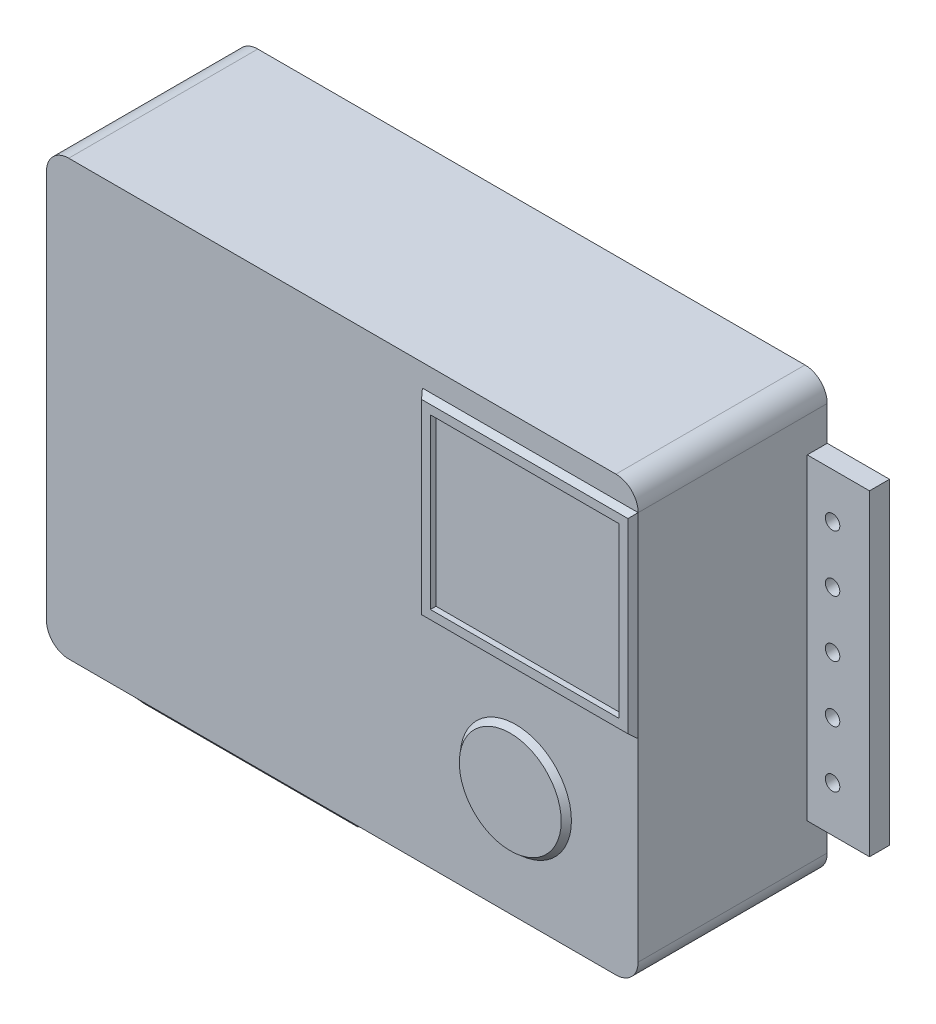
SolidWorks part; units mm, degrees
ref_plane "Front Plane" through (0, 0, 0) normal (0, 0, 1) x (1, 0, 0)
ref_plane "Top Plane" through (0, 0, 0) normal (0, 1, 0) x (1, 0, 0)
ref_plane "Right Plane" through (0, 0, 0) normal (1, 0, 0) x (0, 0, -1)
sketch "Sketch1" plane through (0, 0, 0) normal (0, 0, 1) x (1, 0, 0)
  line L0 (0, 9.75) -> (0, -9.75) construction
  line L1 (-13.3, 9.75) -> (13.3, 9.75)
  line L2 (-13.3, 9.75) -> (-13.3, -9.75)
  line L3 (-13.3, -9.75) -> (13.3, -9.75)
  line L4 (13.3, 9.75) -> (13.3, -9.75)
  point P6 (0, 0)
  point P7 (0, 0)
  dimension "D1" = 26.6
  dimension "D2" = 19.5
extrude "Base" add sketch "Sketch1" along normal blind 8.5
sketch "Sketch2" plane through (0, 0, 8.5) normal (0, 0, 1) x (1, 0, 0)
  line L0 (13.3, -9.75) -> (13.3, 9.75) construction
  line L1 (3.6, 8.75) -> (13.3, 8.75)
  line L2 (3.6, 8.75) -> (3.6, -0.05)
  line L3 (3.6, -0.05) -> (13.3, -0.05)
  line L4 (13.3, 8.75) -> (13.3, -0.05)
  line L6 (13.3, 9.75) -> (-13.3, 9.75) construction
  line L7 (-13.3, -9.75) -> (13.3, -9.75) construction
  circle A0 centre (7.8, -4.75) radius 2.5
  dimension "D1" = 5
  dimension "D5" = 5
  dimension "D6" = 5.5
  dimension "D2" = 8.8
  dimension "D3" = 9.7
  dimension "D4" = 1
extrude "Boss-Extrude2" add sketch "Sketch2" along normal blind 0.25 draft 40
sketch "Sketch3" plane through (0, 0, 8.75) normal (0, 0, 1) x (1, 0, 0)
  line L8 (12.6902, 8.1402) -> (4.2098, 8.1402)
  line L9 (12.6902, 0.5598) -> (12.6902, 8.1402)
  line L10 (4.2098, 0.5598) -> (12.6902, 0.5598)
  line L11 (4.2098, 8.1402) -> (4.2098, 0.5598)
  line L12 (12.6902, 8.1402) -> (4.2098, 8.1402)
  line L13 (12.6902, 0.5598) -> (12.6902, 8.1402)
  line L14 (4.2098, 0.5598) -> (12.6902, 0.5598)
  line L15 (4.2098, 8.1402) -> (4.2098, 0.5598)
  dimension "D1" = 0.4
extrude "Cut-Extrude1" cut sketch "Sketch3" against normal up to surface (0.25 mm away) up to face at (10.3, -4.75, 8.5)
sketch "Sketch4" plane through (0, -9.75, 0) normal (0, -1, 0) x (1, 0, 0)
  line L0 (-13.3, 8.5) -> (13.3, 8.5) construction
  line L1 (-9.3, 8.5) -> (0.7, 8.5)
  line L2 (-9.3, 8.5) -> (-9.3, 0)
  line L3 (-9.3, 0) -> (0.7, 0)
  line L4 (0.7, 8.5) -> (0.7, 0)
  line L5 (-13.3, 0) -> (13.3, 0) construction
  line L6 (-13.3, 8.5) -> (-13.3, 0) construction
  dimension "D1" = 10
  dimension "D2" = 4
extrude "Boss-Extrude3" add sketch "Sketch4" along normal blind 0.25 draft 40
sketch "Sketch5" plane through (0, -10, 0) normal (0, -1, 0) x (1, 0, 0)
  line L8 (-8.7902, 7.9902) -> (-8.7902, 0.5098)
  line L9 (-8.7902, 0.5098) -> (0.1902, 0.5098)
  line L10 (0.1902, 0.5098) -> (0.1902, 7.9902)
  line L11 (0.1902, 7.9902) -> (-8.7902, 7.9902)
  line L12 (-8.7902, 7.9902) -> (-8.7902, 0.5098)
  line L13 (-8.7902, 0.5098) -> (0.1902, 0.5098)
  line L14 (0.1902, 0.5098) -> (0.1902, 7.9902)
  line L15 (0.1902, 7.9902) -> (-8.7902, 7.9902)
  dimension "D1" = 0.3
extrude "Cut-Extrude2" cut sketch "Sketch5" against normal up to surface (0.25 mm away) up to face at (-11.3, -9.75, 4.25)
fillet "Fillet1" radius 1 4 edges at (13.3, 9.75, 4.25) (13.3, -9.75, 4.25) (-13.3, 9.75, 4.25) (-13.3, -9.75, 4.25)
sketch "Sketch6" plane through (0, 0, 0) normal (0, 0, -1) x (-1, 0, 0)
  line L0 (-12.3, 9.75) -> (12.3, 9.75) construction
  line L1 (4.2, 3.55) -> (-2.3, 3.55)
  line L2 (4.2, 3.55) -> (4.2, 6.05)
  line L3 (4.2, 6.05) -> (-2.3, 6.05)
  line L4 (-2.3, 3.55) -> (-2.3, 6.05)
  line L5 (13.3, 8.75) -> (13.3, -8.75) construction
  dimension "D1" = 6.5
  dimension "D2" = 2.5
  dimension "D3" = 3.7
  dimension "D4" = 9.1
extrude "Connector1" add sketch "Sketch6" along normal blind 0.2
sketch "Sketch7" plane through (0, 0, -0.2) normal (0, 0, -1) x (-1, 0, 0)
  line L1 (3.2, 3.7) -> (-1.3, 3.7)
  line L2 (3.2, 3.7) -> (3.2, 5.9)
  line L3 (3.2, 5.9) -> (-1.3, 5.9)
  line L4 (-1.3, 3.7) -> (-1.3, 5.9)
  line L6 (0.95, 6.05) -> (0.95, 3.55) construction
  line L7 (4.2, 6.05) -> (-2.3, 6.05) construction
  line L8 (-2.3, 3.55) -> (4.2, 3.55) construction
  line L9 (0.95, 3.7) -> (0.95, 5.9) construction
  point P8 (0.9, 6.05)
  point P9 (0.95, 4.8)
  point P14 (0, 0)
  point P15 (0.95, 4.8)
  dimension "D1" = 4.5
  dimension "D2" = 2.2
extrude "Connector2" add sketch "Sketch7" along normal blind 0.25
sketch "Sketch8" plane through (0, 0, 0) normal (0, 0, -1) x (-1, 0, 0)
  line L0 (13.3, 8.75) -> (13.3, -8.75) construction
  line L1 (13.3, -7.75) -> (16.6, -7.75)
  line L2 (13.3, -7.75) -> (13.3, 5.25)
  line L3 (13.3, 5.25) -> (16.6, 5.25)
  line L4 (16.6, -7.75) -> (16.6, 5.25)
  line L5 (-13.3, -8.75) -> (-13.3, 8.75) construction
  line L6 (-13.3, -7.05) -> (-16.1, -7.05)
  line L7 (-13.3, -7.05) -> (-13.3, 7.2)
  line L8 (-13.3, 7.2) -> (-16.1, 7.2)
  line L9 (-16.1, -7.05) -> (-16.1, 7.2)
  line L10 (12.3, -9.75) -> (9.3, -9.75) construction
  line L11 (-0.7, -9.75) -> (-12.3, -9.75) construction
  dimension "D1" = 13
  dimension "D2" = 14.25
  dimension "D3" = 2
  dimension "D4" = 3.3
  dimension "D5" = 2.7
  dimension "D6" = 2.8
extrude "PCB" add sketch "Sketch8" against normal blind 0.9
sketch "Sketch9" plane through (0, 0, 0) normal (0, 0, -1) x (-1, 0, 0)
  line L1 (12.3, -9.75) -> (9.3, -9.75) construction
  line L2 (13.3, -7.75) -> (16.6, -7.75) construction
  line L3 (16.6, -7.75) -> (16.6, 5.25) construction
  line L4 (-16.1, 7.2) -> (-16.1, -7.05) construction
  line L6 (-16.1, -7.05) -> (-13.3, -7.05) construction
  line L7 (16.6, 5.25) -> (13.3, 5.25) construction
  circle A0 centre (15.1, -5.05) radius 0.325
  circle A1 centre (15.1, -2.51) radius 0.325
  circle A2 centre (15.1, 0.03) radius 0.325
  circle A3 centre (15.1, 2.57) radius 0.325
  circle A4 centre (-14.44, -5) radius 0.325
  circle A5 centre (-14.44, -2.46) radius 0.325
  circle A6 centre (-14.44, 0.08) radius 0.325
  circle A7 centre (-14.44, 2.62) radius 0.325
  circle A8 centre (-14.44, 5.16) radius 0.325
  point P30 (-14.7, -7.05)
  dimension "D1" = 0.65
  dimension "D7" = 29.54
  dimension "D8" = 2.54
  dimension "D10" = 2.05
  dimension "D11" = 2.54
  dimension "D12" = 2.68
  dimension "D2" = 4.7
  dimension "D3" = 2.7
  dimension "D4" = 32.7
  dimension "D5" = 1.5
  dimension "D6" = 4
  dimension "D9" = 5
extrude "Cut-Extrude3" cut sketch "Sketch9" against normal up to next
